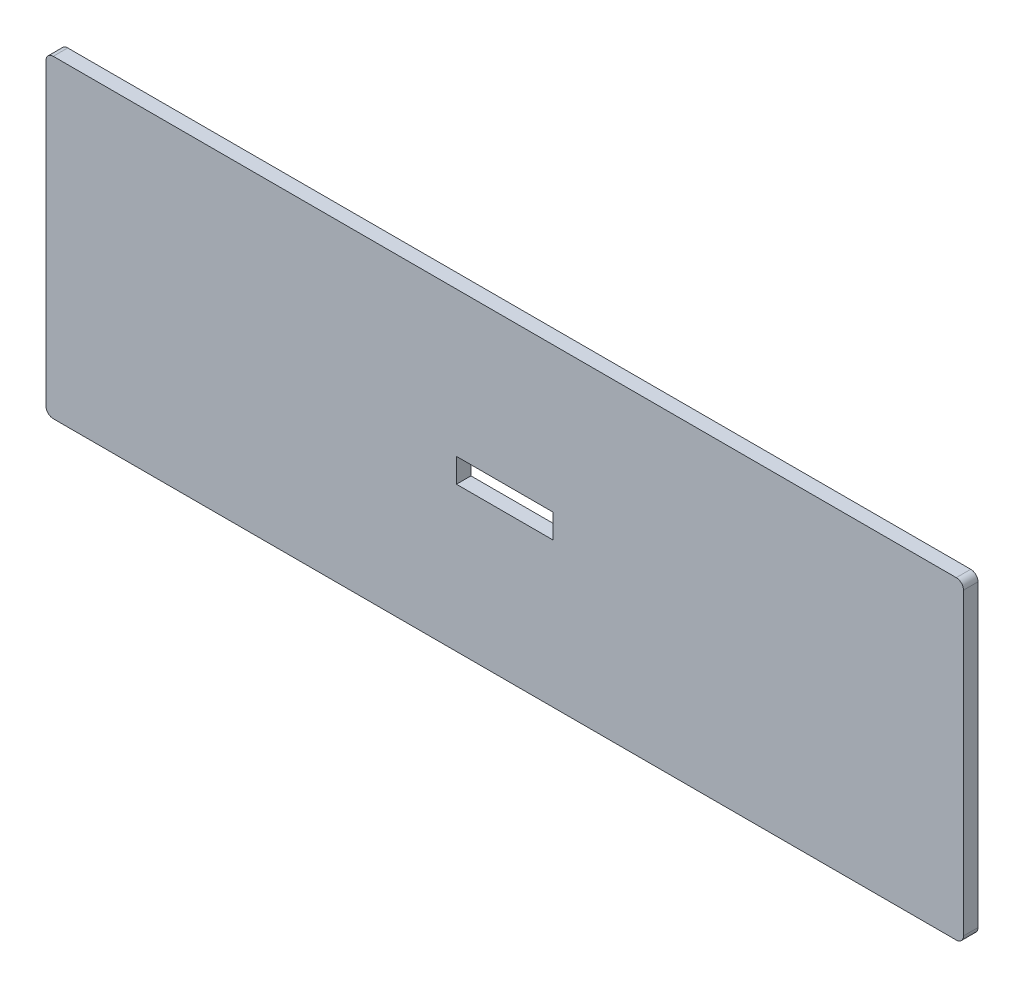
SolidWorks part; units mm, degrees
ref_plane "Front Plane" through (0, 0, 0) normal (0, 0, 1) x (1, 0, 0)
ref_plane "Top Plane" through (0, 0, 0) normal (0, 1, 0) x (1, 0, 0)
ref_plane "Right Plane" through (0, 0, 0) normal (1, 0, 0) x (0, 0, -1)
sketch "Sketch2" plane through (0, 0, 0) normal (0, 0, 1) x (1, 0, 0)
  line L0 (95, 65) -> (95, 0) construction
  line L1 (0, 0) -> (190, 0)
  line L2 (0, 0) -> (0, 65)
  line L3 (0, 65) -> (190, 65)
  line L4 (190, 0) -> (190, 65)
  line L6 (85, 35) -> (105, 35)
  line L7 (85, 35) -> (85, 30)
  line L8 (85, 30) -> (105, 30)
  line L9 (105, 35) -> (105, 30)
  dimension "D1" = 190
  dimension "D2" = 65
  dimension "D3" = 5
  dimension "D4" = 20
  dimension "D5" = 10
  dimension "D6" = 30
extrude "Boss-Extrude1" add sketch "Sketch2" along normal blind 3
fillet "Fillet1" radius 1.5 4 edges at (0, 0, 1.5) (190, 0, 1.5) (190, 65, 1.5) (0, 65, 1.5)
